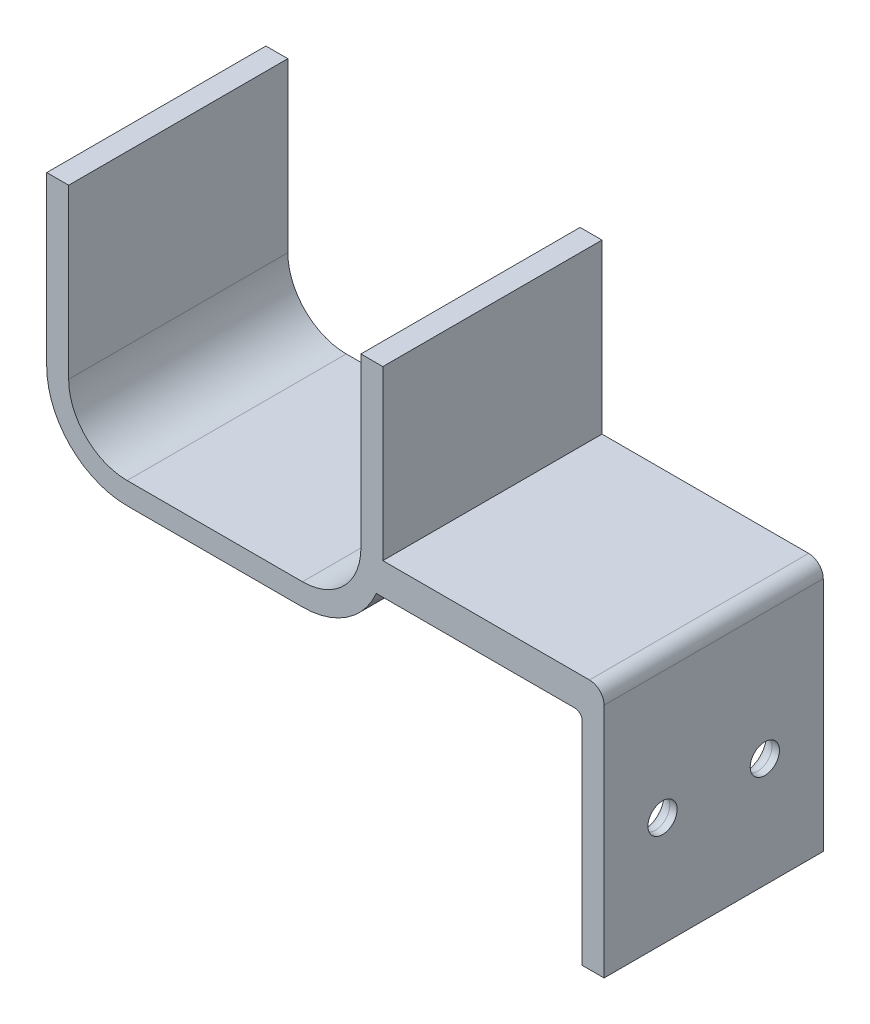
SolidWorks part; units mm, degrees
ref_plane "Front Plane" through (0, 0, 0) normal (0, 0, 1) x (1, 0, 0)
ref_plane "Top Plane" through (0, 0, 0) normal (0, 1, 0) x (1, 0, 0)
ref_plane "Right Plane" through (0, 0, 0) normal (1, 0, 0) x (0, 0, -1)
sketch "Sketch1" plane through (0, 0, 0) normal (0, 0, 1) x (1, 0, 0)
  line L0 (-12, 34) -> (12, 34)
  line L1 (-12, 31) -> (12, 31)
  line L2 (-20, 23) -> (-20, -23)
  line L3 (-12, -31) -> (12, -31)
  line L4 (20, 23) -> (20, -23)
  line L5 (23, 23) -> (23, -23)
  line L6 (-12, -34) -> (12, -34)
  line L7 (-23, 23) -> (-23, -23)
  arc A0 (-12, 31) -> (-20, 23) centre (-12, 23) ccw
  arc A1 (-20, -23) -> (-12, -31) centre (-12, -23) ccw
  arc A2 (12, -31) -> (20, -23) centre (12, -23) ccw
  arc A3 (12, 31) -> (20, 23) centre (12, 23) cw
  arc A4 (12, 34) -> (23, 23) centre (12, 23) cw
  arc A5 (12, -34) -> (23, -23) centre (12, -23) ccw
  arc A6 (-23, -23) -> (-12, -34) centre (-12, -23) ccw
  arc A7 (-12, 34) -> (-23, 23) centre (-12, 23) ccw
  point P0 (0, 0)
  dimension "D3" = 8
  dimension "D4" = 8
  dimension "D1" = 3
extrude "Boss-Extrude1" add sketch "Sketch1" along normal blind 30
sketch "Sketch2" plane through (0, 0, 0) normal (0, 0, 1) x (1, 0, 0)
  line L0 (23, -23) -> (53.2825, -23)
  line L1 (53.2825, -23) -> (53.2825, -27.3296)
  line L2 (53.2825, -27.3296) -> (22.1121, -27.3296)
  line L3 (53.2825, 129.2876) -> (53.2825, -81.0694) construction
  arc A0 (12, -34) -> (23, -23) centre (12, -23) ccw construction
  arc A1 (22.1121, -27.3296) -> (23, -23) centre (12, -23) ccw
extrude "Boss-Extrude2" add sketch "Sketch2" along normal blind 30
sketch "Sketch3" plane through (0, -27.3296, 0) normal (0, -1, 0) x (1, 0, 0)
  line L0 (22.1121, 30) -> (53.2825, 30) construction
  line L1 (53.2825, 0) -> (50.2825, 0)
  line L2 (53.2825, 0) -> (53.2825, 30)
  line L3 (53.2825, 30) -> (50.2825, 30)
  line L4 (50.2825, 0) -> (50.2825, 30)
  dimension "D1" = 3
extrude "Boss-Extrude3" add sketch "Sketch3" along normal blind 30
fillet "Fillet1" radius 1 1 edges at (50.2825, -27.3296, 15)
fillet "Fillet2" radius 2 1 edges at (53.2825, -23, 15)
sketch "Sketch4" plane through (50.2825, 0, 0) normal (-1, 0, 0) x (0, 0, 1)
  line L0 (0, -57.3296) -> (0, -28.3296) construction
  line L1 (30, -57.3296) -> (30, -28.3296) construction
  line L2 (30, -57.3296) -> (0, -57.3296) construction
  circle A0 centre (22, -42.3296) radius 2
  circle A1 centre (8, -42.3296) radius 2
  dimension "D4" = 4
  dimension "D1" = 8
  dimension "D2" = 8
  dimension "D3" = 15
extrude "Cut-Extrude1" cut sketch "Sketch4" against normal blind 30
fillet "Fillet3" radius 2 2 edges at (50.2825, -44.3296, 22) (50.2825, -44.3296, 8)
sketch "Sketch6" plane through (0, 0, 0) normal (0, 0, -1) x (-1, 0, 0)
  line L1 (-36.6152, 0) -> (44.1037, 0)
  line L2 (-36.6152, 0) -> (-36.6152, 35.9804)
  line L3 (-36.6152, 35.9804) -> (44.1037, 35.9804)
  line L4 (44.1037, 0) -> (44.1037, 35.9804)
extrude "Cut-Extrude2" cut sketch "Sketch6" against normal through all
